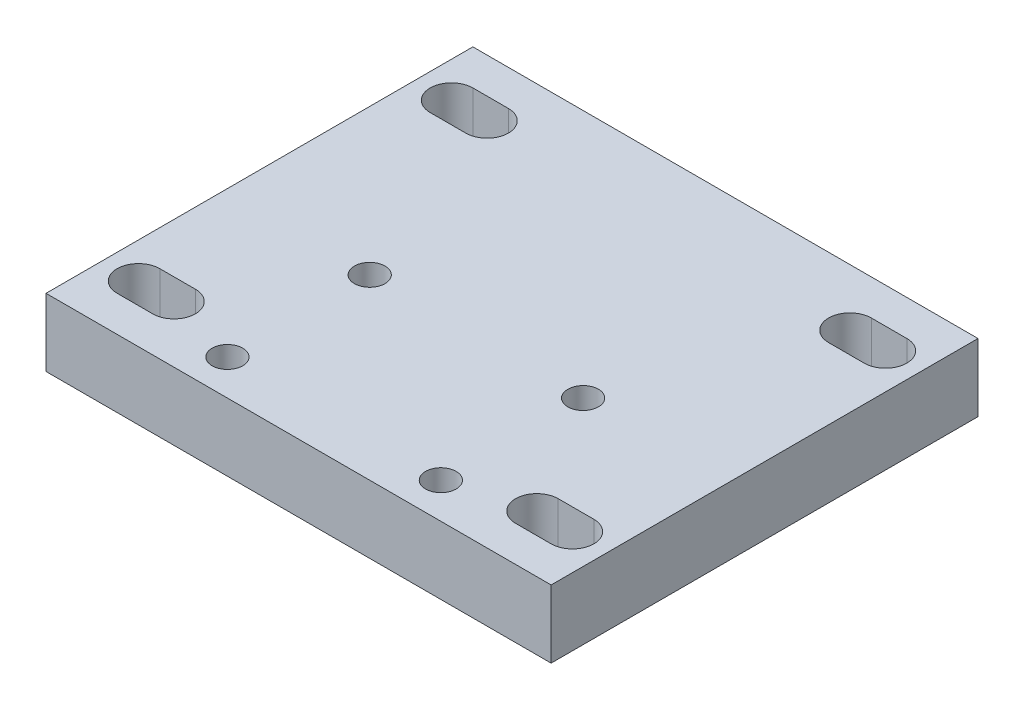
SolidWorks part; units mm, degrees
ref_plane "Alzado" through (0, 0, 0) normal (0, 0, 1) x (1, 0, 0)
ref_plane "Planta" through (0, 0, 0) normal (0, 1, 0) x (1, 0, 0)
ref_plane "Vista lateral" through (0, 0, 0) normal (1, 0, 0) x (0, 0, -1)
sketch "Croquis1" plane through (0, 0, 0) normal (0, 0, 1) x (1, 0, 0)
  line L0 (18, 7.24) -> (18, 2.24) construction
  line L1 (71, 0) -> (0, 0)
  line L2 (71, 0) -> (71, 9.52)
  line L3 (71, 9.52) -> (0, 9.52)
  line L4 (0, 0) -> (0, 9.52)
  line L5 (54, 7.24) -> (54, 2.24) construction
  line L6 (0, 4.76) -> (71, 4.76) construction
  circle A0 centre (18, 4.74) radius 2.38
  circle A1 centre (54, 4.74) radius 2.38
  circle A2 centre (54, 4.74) radius 2.38
  circle A3 centre (18, 4.74) radius 2.38
  dimension "D2" = 4.74
  dimension "D3" = 4.74
  dimension "D4" = 36
  dimension "D5" = 18
  dimension "D7" = 4.76
  dimension "D8" = 9.52
  dimension "D1" = 71
  dimension "D6" = 9.52
sketch "Croquis2" plane through (0, 0, 0) normal (0, 0, 1) x (1, 0, 0)
  line L1 (0, 0) -> (71, 0)
  line L2 (0, 0) -> (0, 9.52)
  line L3 (0, 9.52) -> (71, 9.52)
  line L4 (71, 0) -> (71, 9.52)
extrude "Saliente-Extruir1" add sketch "Croquis2" along normal blind 60
sketch "Croquis3" plane through (0, 0, 0) normal (0, 0, -1) x (-1, 0, 0)
  circle A0 centre (-54, 4.74) radius 2.38
  circle A1 centre (-18, 4.74) radius 2.38
  dimension "D1" = 4.76
extrude "Cortar-Extruir1" cut sketch "Croquis3" against normal blind 15
sketch "Croquis4" plane through (0, 9.52, 0) normal (0, 1, 0) x (1, 0, 0)
  line L0 (61, -8) -> (66, -8) construction
  line L3 (61, -5) -> (66, -5)
  line L8 (61, -11) -> (66, -11)
  line L11 (71, 0) -> (0, 0) construction
  line L18 (71, -60) -> (71, 0) construction
  line L19 (61, -52) -> (66, -52) construction
  line L20 (61, -49) -> (66, -49)
  line L21 (61, -55) -> (66, -55)
  line L22 (71, -60) -> (0, -60) construction
  line L23 (5, -8) -> (10, -8) construction
  line L24 (5, -5) -> (10, -5)
  line L25 (5, -11) -> (10, -11)
  line L27 (0, -60) -> (0, 0) construction
  line L28 (5, -52) -> (10, -52) construction
  line L29 (5, -49) -> (10, -49)
  line L30 (5, -55) -> (10, -55)
  arc A8 (61, -5) -> (61, -11) centre (61, -8) ccw
  arc A9 (66, -11) -> (66, -5) centre (66, -8) ccw
  arc A10 (61, -49) -> (61, -55) centre (61, -52) ccw
  arc A11 (66, -55) -> (66, -49) centre (66, -52) ccw
  arc A12 (5, -5) -> (5, -11) centre (5, -8) ccw
  arc A13 (10, -11) -> (10, -5) centre (10, -8) ccw
  arc A14 (5, -49) -> (5, -55) centre (5, -52) ccw
  arc A15 (10, -55) -> (10, -49) centre (10, -52) ccw
  point P2 (63.5, -8)
  point P10 (63.5, -52)
  point P21 (7.5, -8)
  point P30 (7.5, -52)
  dimension "D3" = 2
  dimension "D8" = 2
  dimension "D1" = 6
  dimension "D2" = 5
  dimension "D4" = 5
  dimension "D5" = 5
  dimension "D6" = 5
  dimension "D7" = 5
  dimension "D9" = 5
extrude "Cortar-Extruir2" cut sketch "Croquis4" against normal up to next
sketch "Croquis5" plane through (0, 0, 0) normal (0, -1, 0) x (1, 0, 0)
  line L1 (0, 60) -> (71, 60) construction
  line L2 (20.5, 55) -> (50.5, 55) construction
  line L3 (35.5, 0) -> (35.5, 55) construction
  line L4 (0, 0) -> (71, 0) construction
  point P0 (20.5, 55)
  point P1 (20.5, 35)
  point P2 (50.5, 35)
  point P3 (50.5, 55)
  dimension "D1" = 20
  dimension "D2" = 5
  dimension "D3" = 30
hole_wizard "Refrentado para tornillo tapón con cabeza de clavija de M41" positions "Croquis6" profile "Croquis7" counterbore size "M4" standard "Ansi Metric"
sketch "Croquis6" plane through (0, 0, 0) normal (0, -1, 0) x (-1, 0, 0)
  point P0 (-50.5, -35)
  point P3 (-50.5, -55)
  point P6 (-20.5, -55)
  point P9 (-20.5, -35)
sketch "Croquis7" plane through (50.5, 0, 35) normal (1, 0, 0) x (0, 0, -1)
  line L0 (0, 0) -> (0, 18.2919)
  line L1 (0, 18.2919) -> (2.15, 17)
  line L2 (2.15, 17) -> (2.15, 4)
  line L3 (2.15, 4) -> (3.75, 4)
  line L4 (3.75, 4) -> (3.75, 0)
  line L5 (3.75, 0) -> (0, 0)
  line L10 (0, 18.2919) -> (-2.15, 17) construction
  line L11 (0, -6.35) -> (0, 107.95) construction
  dimension "Diámetro de taladro" = 4.3
  dimension "Profundidad de taladro" = 17
  dimension "Diámetro de refrentado" = 7.5
  dimension "Profundidad de refrentado" = 4
  dimension "Ángulo de perforador" = 118
